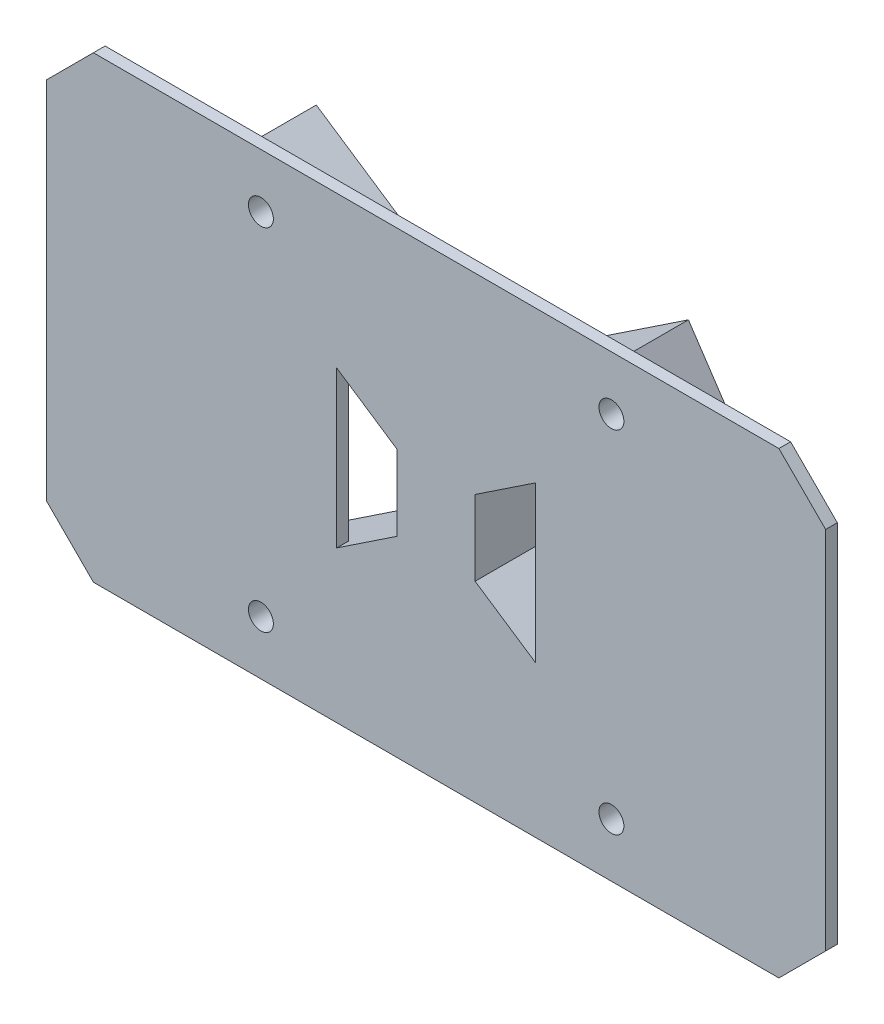
SolidWorks part; units mm, degrees
ref_plane "Front Plane" through (0, 0, 0) normal (0, 0, 1) x (1, 0, 0)
ref_plane "Top Plane" through (0, 0, 0) normal (0, 1, 0) x (1, 0, 0)
ref_plane "Right Plane" through (0, 0, 0) normal (1, 0, 0) x (0, 0, -1)
sketch "Sketch1" plane through (0, 0, 0) normal (0, 0, 1) x (1, 0, 0)
  line L0 (0, 7.5) -> (0, -7.5) construction
  line L1 (-22.5, 22.5) -> (22.5, 22.5) construction
  line L2 (-22.5, 22.5) -> (-22.5, -22.5) construction
  line L3 (-22.5, -22.5) -> (22.5, -22.5) construction
  line L4 (22.5, 22.5) -> (22.5, -22.5) construction
  line L5 (-22.5, 22.5) -> (22.5, -22.5) construction
  line L6 (-22.5, -22.5) -> (22.5, 22.5) construction
  line L7 (-22.5, 22.5) -> (0, 7.5) construction
  line L8 (22.5, 22.5) -> (0, 7.5) construction
  line L9 (-5, 4.8241) -> (-5, -4.8241)
  line L11 (-25.2735, 18.3397) -> (-5, 4.8241)
  line L12 (19.7265, 26.6603) -> (0, 13.5093)
  line L13 (-19.7265, 26.6603) -> (0, 13.5093)
  line L14 (25.2735, 18.3397) -> (5, 4.8241)
  line L16 (-21.1132, 15.5662) -> (-29.4338, 21.1132)
  line L17 (-15.5662, 23.8868) -> (-23.8868, 29.4338)
  line L18 (-29.4338, 21.1132) -> (-23.8868, 29.4338)
  line L19 (-21.1132, 15.5662) -> (-23.8868, 29.4338) construction
  line L20 (-15.5662, 23.8868) -> (-29.4338, 21.1132) construction
  line L21 (0, 0) -> (22.5, 0) construction
  line L22 (15.5662, 23.8868) -> (23.8868, 29.4338)
  line L23 (29.4338, 21.1132) -> (23.8868, 29.4338)
  line L24 (21.1132, 15.5662) -> (29.4338, 21.1132)
  line L26 (25.2735, -18.3397) -> (5, -4.8241)
  line L27 (-25.2735, -18.3397) -> (-5, -4.8241)
  line L28 (-19.7265, -26.6603) -> (0, -13.5093)
  line L29 (19.7265, -26.6603) -> (0, -13.5093)
  line L31 (21.1132, -15.5662) -> (29.4338, -21.1132)
  line L32 (29.4338, -21.1132) -> (23.8868, -29.4338)
  line L33 (15.5662, -23.8868) -> (23.8868, -29.4338)
  line L34 (-15.5662, -23.8868) -> (-23.8868, -29.4338)
  line L35 (-29.4338, -21.1132) -> (-23.8868, -29.4338)
  line L36 (-21.1132, -15.5662) -> (-29.4338, -21.1132)
  line L38 (-5, 7.5) -> (-5, -7.5) construction
  line L39 (-25.2735, 18.3397) -> (-2.7735, 3.3397) construction
  line L40 (19.7265, 26.6603) -> (-2.7735, 11.6603) construction
  line L41 (-19.7265, 26.6603) -> (2.7735, 11.6603) construction
  line L43 (25.2735, 18.3397) -> (2.7735, 3.3397) construction
  line L44 (5, 4.8241) -> (5, -4.8241)
  circle A0 centre (-22.5, 22.5) radius 1.6
  circle A1 centre (22.5, 22.5) radius 1.6
  circle A2 centre (22.5, -22.5) radius 1.6
  circle A3 centre (-22.5, -22.5) radius 1.6
  point P0 (0, 0)
  point P16 (0, 0)
  point P17 (0, 0)
  dimension "D2" = 3.2
  dimension "D1" = 45
  dimension "D4" = 15
  dimension "D9" = 10
  dimension "D5" = 5
  dimension "D7" = 5
  dimension "D8" = 5
  dimension "D3" = 4
extrude "Boss-Extrude1" add sketch "Sketch1" along normal blind 7 contours L44 L14 L24 L23 L22 L12 L13 L17 L18 L16 L11 L9 L27 L36 L35 L34 L28 L29 L33 L32 L31 L26 A3 A2 A1 A0
sketch "Sketch2" plane through (0, 0, 7) normal (0, 0, 1) x (1, 0, 0)
  line L1 (-50, 29.4338) -> (50, 29.4338)
  line L2 (-50, 29.4338) -> (-50, -29.4338)
  line L3 (-50, -29.4338) -> (50, -29.4338)
  line L4 (50, 29.4338) -> (50, -29.4338)
  line L5 (-12.7639, -10) -> (12.7639, -10)
  line L6 (-12.7639, -10) -> (-12.7639, 10)
  line L7 (-12.7639, 10) -> (12.7639, 10)
  line L8 (12.7639, -10) -> (12.7639, 10)
  line L9 (-12.7639, -10) -> (12.7639, 10) construction
  line L10 (-12.7639, 10) -> (12.7639, -10) construction
  line L11 (-50, 29.4338) -> (50, -29.4338) construction
  line L12 (-50, -29.4338) -> (50, 29.4338) construction
  line L14 (5, -4.8241) -> (5, 4.8241)
  line L15 (5, 4.8241) -> (29.4338, 21.1132)
  line L16 (29.4338, 21.1132) -> (23.8868, 29.4338)
  line L17 (23.8868, 29.4338) -> (0, 13.5093)
  line L18 (0, 13.5093) -> (-23.8868, 29.4338)
  line L19 (-23.8868, 29.4338) -> (-29.4338, 21.1132)
  line L20 (-29.4338, 21.1132) -> (-5, 4.8241)
  line L21 (-5, 4.8241) -> (-5, -4.8241)
  line L22 (-5, -4.8241) -> (-29.4338, -21.1132)
  line L23 (-29.4338, -21.1132) -> (-23.8868, -29.4338)
  line L24 (-23.8868, -29.4338) -> (0, -13.5093)
  line L25 (0, -13.5093) -> (23.8868, -29.4338)
  line L26 (23.8868, -29.4338) -> (29.4338, -21.1132)
  line L27 (29.4338, -21.1132) -> (5, -4.8241)
  line L28 (5, -4.8241) -> (5, 4.8241)
  line L29 (5, 4.8241) -> (12.7639, 10)
  line L34 (-12.7639, 10) -> (-5, 4.8241)
  line L35 (-5, 4.8241) -> (-5, -4.8241)
  line L36 (-5, -4.8241) -> (-12.7639, -10)
  line L41 (12.7639, -10) -> (5, -4.8241)
  line L48 (5, -4.8241) -> (5, 4.8241)
  line L49 (29.4338, -21.1132) -> (5, -4.8241)
  line L50 (23.8868, -29.4338) -> (29.4338, -21.1132)
  line L51 (0, -13.5093) -> (23.8868, -29.4338)
  line L52 (-23.8868, -29.4338) -> (0, -13.5093)
  line L53 (-29.4338, -21.1132) -> (-23.8868, -29.4338)
  line L54 (-5, -4.8241) -> (-29.4338, -21.1132)
  line L55 (-5, 4.8241) -> (-5, -4.8241)
  line L56 (-29.4338, 21.1132) -> (-5, 4.8241)
  line L57 (-23.8868, 29.4338) -> (-29.4338, 21.1132)
  line L58 (0, 13.5093) -> (-23.8868, 29.4338)
  line L59 (23.8868, 29.4338) -> (0, 13.5093)
  line L60 (29.4338, 21.1132) -> (23.8868, 29.4338)
  line L61 (5, 4.8241) -> (29.4338, 21.1132)
  line L62 (5, -4.8241) -> (5, 4.8241)
  line L63 (29.4338, -21.1132) -> (5, -4.8241)
  line L64 (23.8868, -29.4338) -> (29.4338, -21.1132)
  line L65 (0, -13.5093) -> (23.8868, -29.4338)
  line L66 (-23.8868, -29.4338) -> (0, -13.5093)
  line L67 (-29.4338, -21.1132) -> (-23.8868, -29.4338)
  line L68 (-5, -4.8241) -> (-29.4338, -21.1132)
  line L69 (-5, 4.8241) -> (-5, -4.8241)
  line L70 (-29.4338, 21.1132) -> (-5, 4.8241)
  line L71 (-23.8868, 29.4338) -> (-29.4338, 21.1132)
  line L72 (0, 13.5093) -> (-23.8868, 29.4338)
  line L73 (23.8868, 29.4338) -> (0, 13.5093)
  line L74 (29.4338, 21.1132) -> (23.8868, 29.4338)
  line L75 (5, 4.8241) -> (29.4338, 21.1132)
  point P2 (0, 0)
  point P16 (0, 0)
  dimension "D2" = 20
  dimension "D4" = 100
  dimension "D1" = 0
  dimension "D3" = 0
extrude "Boss-Extrude2" add sketch "Sketch2" along normal blind 1.5
chamfer "Chamfer1" distance 6 angle 45 1 edges at (-50, -29.4338, 7.75)
chamfer "Chamfer2" distance 6 angle 45 3 edges at (50, -29.4338, 7.75) (50, 29.4338, 7.75) (-50, 29.4338, 7.75)
